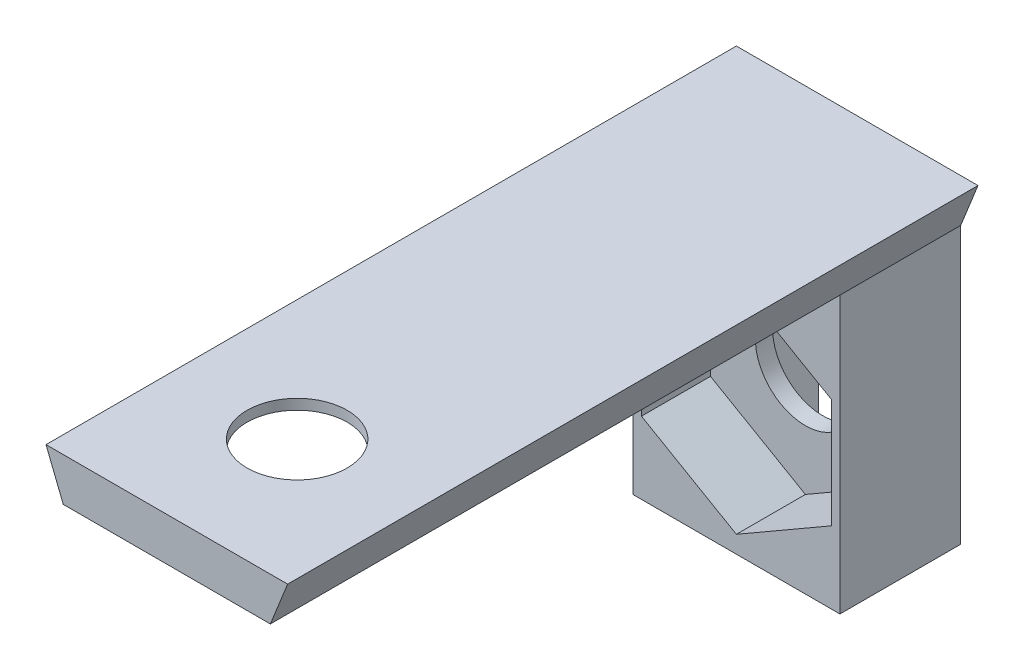
SolidWorks part; units mm, degrees
ref_plane "Front Plane" through (0, 0, 0) normal (0, 0, 1) x (1, 0, 0)
ref_plane "Top Plane" through (0, 0, 0) normal (0, 1, 0) x (1, 0, 0)
ref_plane "Right Plane" through (0, 0, 0) normal (1, 0, 0) x (0, 0, -1)
sketch "Sketch1" plane through (0, 0, 0) normal (0, 1, 0) x (1, 0, 0)
  line L1 (-6, -3.5) -> (6, -3.5)
  line L2 (-6, -3.5) -> (-6, 3.5)
  line L3 (-6, 3.5) -> (6, 3.5)
  line L4 (6, -3.5) -> (6, 3.5)
  line L5 (-6, -3.5) -> (6, 3.5) construction
  line L6 (-6, 3.5) -> (6, -3.5) construction
  point P0 (0, 0)
extrude "Boss-Extrude1" add sketch "Sketch1" along normal blind 16
sketch "Sketch2" plane through (0, 16, 0) normal (0, 1, 0) x (1, 0, 0)
  line L0 (0, 3.5) -> (0, 1.5) construction
  line L1 (6, 3.5) -> (-6, 3.5) construction
  line L22 (0, 3.5) -> (2.25, 3.5)
  line L23 (0, 3.5) -> (-2.25, 3.5)
  line L25 (0, 1.5) -> (4.25, 1.5)
  line L27 (0, 1.5) -> (-4.25, 1.5)
  line L28 (-4.25, 1.5) -> (-2.25, 3.5)
  line L29 (2.25, 3.5) -> (4.25, 1.5)
extrude "Cut-Extrude1" cut sketch "Sketch2" against normal blind 20
sketch "Sketch3" plane through (0, 0, 3.5) normal (0, 0, 1) x (1, 0, 0)
  line L0 (0, 0) -> (0, 7.35) construction
  line L1 (-6, 0) -> (6, 0) construction
  circle A0 centre (0, 7.35) radius 2.9
  point P2 (0, 7.705)
extrude "Cut-Extrude2" cut sketch "Sketch3" against normal up to next
sketch "Sketch4" plane through (0, 0, 3.5) normal (0, 0, 1) x (1, 0, 0)
  line L0 (0, 0) -> (0, 7.35) construction
  line L1 (0, 13.7009) -> (-5.5, 10.5254)
  line L2 (-5.5, 10.5254) -> (-5.5, 4.1746)
  line L3 (-5.5, 4.1746) -> (0, 0.9991)
  line L4 (0, 0.9991) -> (5.5, 4.1746)
  line L5 (5.5, 4.1746) -> (5.5, 10.5254)
  line L6 (5.5, 10.5254) -> (0, 13.7009)
  circle A0 centre (0, 7.35) radius 5.5 construction
  point P1 (0, 0)
  point P13 (0, 0)
  point P14 (0, 7.5275)
extrude "Cut-Extrude3" cut sketch "Sketch4" against normal blind 4
sketch "Sketch5" plane through (0, 16, 0) normal (0, 1, 0) x (1, 0, 0)
  line L0 (-6, 3.5) -> (-7, 3.5) construction
  line L1 (6, 3.5) -> (7, 3.5) construction
  line L3 (-7, 3.5) -> (7, 3.5)
  line L4 (-7, 3.5) -> (-7, -36.5)
  line L5 (-7, -36.5) -> (7, -36.5)
  line L6 (7, 3.5) -> (7, -36.5)
extrude "Boss-Extrude2" add sketch "Sketch5" along normal blind 2.5
sketch "Sketch6" plane through (0, 0, -3.5) normal (0, 0, -1) x (-1, 0, 0)
  line L0 (-7, 16) -> (-7, 18.5)
  line L1 (-7, 18.5) -> (-6, 16)
  line L2 (-6, 16) -> (-7, 16)
  line L3 (7, 16) -> (6, 16)
  line L4 (6, 16) -> (7, 18.5)
  line L5 (7, 18.5) -> (7, 16)
extrude "Cut-Extrude4" cut sketch "Sketch6" against normal up to next
sketch "Sketch8" plane through (0, 16, 0) normal (0, -1, 0) x (1, 0, 0)
  line L1 (0, 22.5991) -> (5.5, 25.7746)
  line L2 (5.5, 25.7746) -> (5.5, 32.1254)
  line L3 (5.5, 32.1254) -> (0, 35.3009)
  line L4 (0, 35.3009) -> (-5.5, 32.1254)
  line L5 (-5.5, 32.1254) -> (-5.5, 25.7746)
  line L6 (-5.5, 25.7746) -> (0, 22.5991)
  line L7 (0, 36.5) -> (0, 28.95) construction
  line L8 (-6, 36.5) -> (6, 36.5) construction
  circle A0 centre (0, 28.95) radius 5.5 construction
extrude "Cut-Extrude6" cut sketch "Sketch8" against normal blind 1.9
sketch "Sketch9" plane through (0, 17.9, 0) normal (0, -1, 0) x (-1, 0, 0)
  circle A0 centre (0, -28.95) radius 2.9
extrude "Cut-Extrude7" cut sketch "Sketch9" against normal up to next
